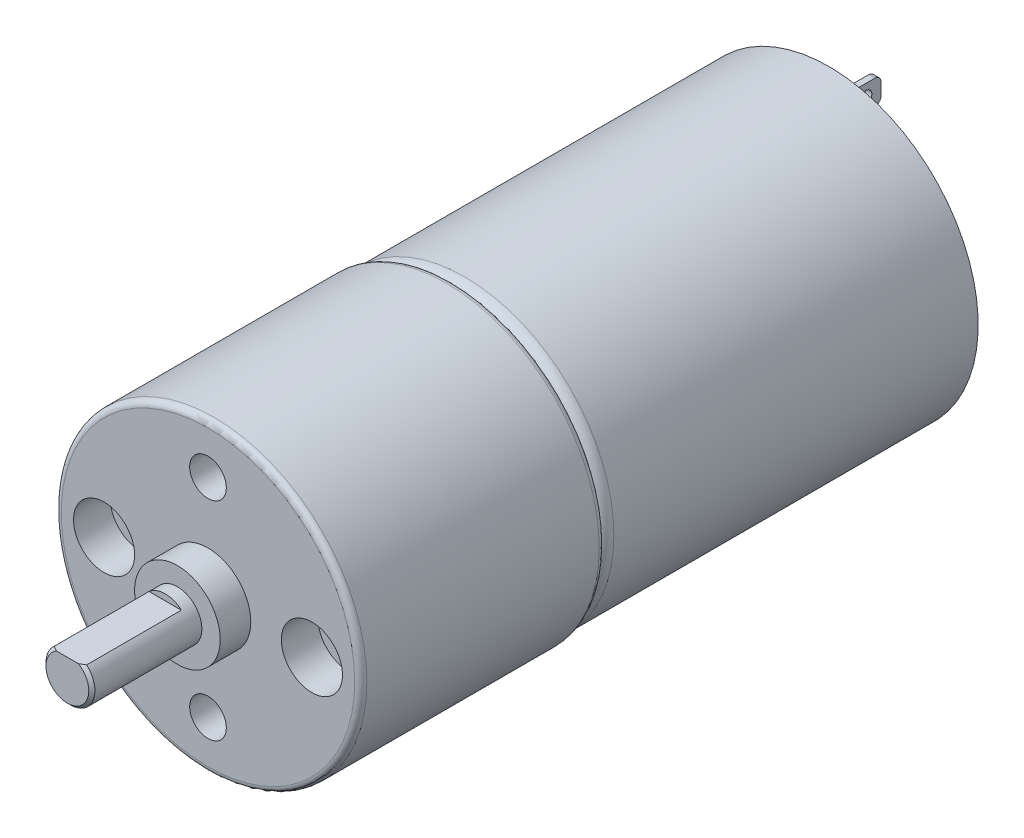
SolidWorks part; units mm, degrees
ref_plane "Front Plane" through (0, 0, 0) normal (0, 0, 1) x (1, 0, 0)
ref_plane "Top Plane" through (0, 0, 0) normal (0, 1, 0) x (1, 0, 0)
ref_plane "Right Plane" through (0, 0, 0) normal (1, 0, 0) x (0, 0, -1)
sketch "Sketch1" plane through (0, 0, 0) normal (0, 0, 1) x (1, 0, 0)
  circle A0 centre (0, 0) radius 12.2
  dimension "24.4" = 24.4
extrude "Boss-Extrude1" add sketch "Sketch1" along normal blind 30.8
fillet "Fillet1" radius 1 1 edges at (12.2, 0, 30.8)
sketch "Sketch2" plane through (0, 0, 0) normal (0, 0, -1) x (-1, 0, 0)
  circle A0 centre (0, 0) radius 3.25
  dimension "D1" = 6.5
extrude "Boss-Extrude2" add sketch "Sketch2" along normal blind 2
sketch "Sketch3" plane through (0, 0, 0) normal (0, 0, -1) x (-1, 0, 0)
  line L0 (0, 8.75) -> (0, -8.75)
  line L1 (8.3134, 0) -> (-8.3134, 0) construction
  line L3 (-0.25, 9.75) -> (0.25, 9.75)
  line L4 (-0.25, 9.75) -> (-0.25, 7.75)
  line L5 (-0.25, 7.75) -> (0.25, 7.75)
  line L6 (0.25, 9.75) -> (0.25, 7.75)
  line L7 (-0.25, 9.75) -> (0.25, 7.75) construction
  line L8 (-0.25, 7.75) -> (0.25, 9.75) construction
  point P4 (0, 0)
  point P8 (0, 0)
  dimension "D1" = 17.5
  dimension "D2" = 0.5
  dimension "D3" = 2
extrude "Boss-Extrude4" add sketch "Sketch3" along normal blind 4 contours L4 L5 L6 L3
sketch "Sketch5" plane through (-0.25, 0, 0) normal (-1, 0, 0) x (0, 0, 1)
  line L0 (-4, 8.75) -> (-2.75, 8.75)
  line L1 (-4, 9.75) -> (-4, 7.75) construction
  circle A0 centre (-2.75, 8.75) radius 0.5
  dimension "D2" = 1
  dimension "D1" = 1.25
extrude "Cut-Extrude2" cut sketch "Sketch5" against normal blind 4 contours A0
fillet "Fillet3" radius 0.5 2 edges at (0, 7.75, -4) (0, 9.75, -4)
mirror "Mirror2" about plane through (0, 0, 0) normal (0, 1, 0) of "Fillet3", "Cut-Extrude2", "Boss-Extrude4"
sketch "Sketch6" plane through (0, 0, 30.8) normal (0, 0, 1) x (1, 0, 0)
  circle A0 centre (0, 0) radius 12.5
  dimension "D1" = 25
extrude "Boss-Extrude5" add sketch "Sketch6" along normal blind 20
fillet "Fillet4" radius 0.5 2 edges at (12.5, 0, 50.8) (12.5, 0, 30.8)
sketch "Sketch7" plane through (0, 0, 50.8) normal (0, 0, 1) x (1, 0, 0)
  circle A0 centre (0, 0) radius 3.5
  dimension "D1" = 7
extrude "Boss-Extrude6" add sketch "Sketch7" along normal blind 2.5
sketch "Sketch8" plane through (0, 0, 53.3) normal (0, 0, 1) x (1, 0, 0)
  circle A0 centre (0, 0) radius 2
  dimension "D1" = 4
extrude "Boss-Extrude7" add sketch "Sketch8" along normal blind 9
sketch "Sketch10" plane through (0, 0, 62.3) normal (0, 0, 1) x (1, 0, 0)
  line L0 (0, 0) -> (0, 1.5)
  line L1 (1.3229, 1.5) -> (-1.3229, 1.5)
  arc A0 (1.3229, 1.5) -> (-1.3229, 1.5) centre (0, 0) ccw
  dimension "D1" = 1.5
extrude "Cut-Extrude3" cut sketch "Sketch10" against normal blind 8 contours A0 L1
chamfer "Chamfer1" distance 0.5 angle 45 1 edges at (-3.25, 0, -2)
sketch "Sketch11" plane through (0, 0, 50.8) normal (0, 0, 1) x (1, 0, 0)
  line L0 (0, -8.5) -> (0, 8.5)
  circle A0 centre (0, -8.5) radius 1.5
  circle A1 centre (0, 8.5) radius 1.5
  dimension "D2" = 3
  dimension "D3" = 3
extrude "Cut-Extrude4" cut sketch "Sketch11" against normal blind 3.5
sketch "Sketch12" plane through (0, 0, 50.8) normal (0, 0, 1) x (1, 0, 0)
  line L0 (-8.5, 0) -> (8.5, 0)
  circle A0 centre (-8.5, 0) radius 2.5
  circle A1 centre (8.5, 0) radius 2.5
  point P2 (0, 0)
  point P4 (0, 0)
  dimension "D2" = 5
  dimension "D3" = 5
  dimension "D1" = 17
extrude "Cut-Extrude5" cut sketch "Sketch12" against normal blind 3
sketch "Sketch13" plane through (0, 0, 47.8) normal (0, 0, 1) x (1, 0, 0)
  line L0 (-8.5, 0) -> (8.5, 0)
  circle A0 centre (8.5, 0) radius 1.25
  circle A1 centre (-8.5, 0) radius 1.25
  point P7 (0, 0)
  dimension "D1" = 2.5
  dimension "2.5" = 2.5
extrude "Cut-Extrude6" cut sketch "Sketch13" against normal blind 3.5 contours A0 | A1
chamfer "Chamfer2" distance 0.25 angle 45 1 edges at (0, -2, 62.3)
